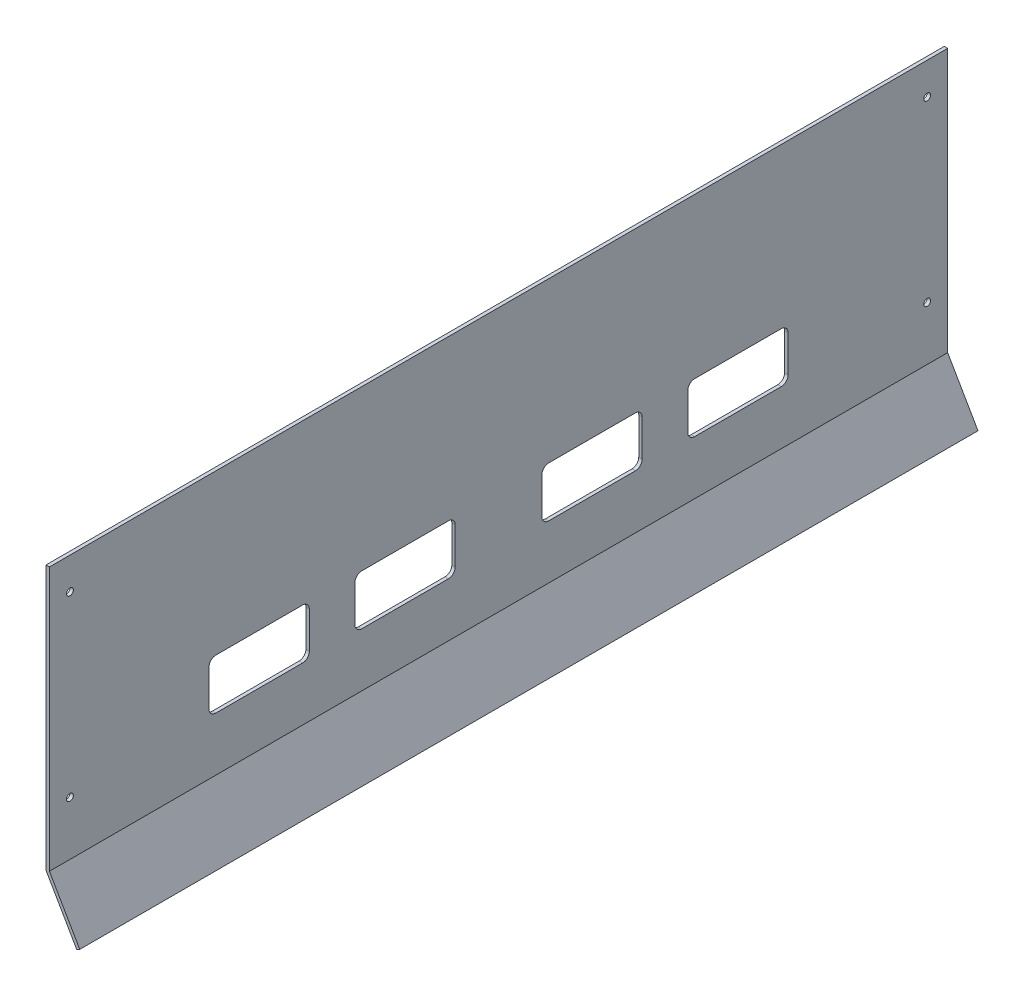
SolidWorks part; units mm, degrees
ref_plane "前视基准面" through (0, 0, 0) normal (0, 0, 1) x (1, 0, 0)
ref_plane "上视基准面" through (0, 0, 0) normal (0, 1, 0) x (1, 0, 0)
ref_plane "右视基准面" through (0, 0, 0) normal (1, 0, 0) x (0, 0, -1)
sketch "草图1" plane through (0, 0, 0) normal (0, 0, 1) x (1, 0, 0)
  line L0 (0, 0) -> (0, 116)
  line L1 (0, 0) -> (13.5, -23.3827)
  line L2 (1.5, 0.4019) -> (14.799, -22.6327)
  line L3 (1.5, 0.4019) -> (1.5, 116)
  line L4 (14.799, -22.6327) -> (13.5, -23.3827)
  line L5 (0, 116) -> (1.5, 116)
  dimension "D1" = 150
  dimension "D2" = 27
  dimension "D3" = 116
  dimension "D4" = 1.5
extrude "凸台-拉伸1" add sketch "草图1" along normal blind 394
sketch "草图2" plane through (0, 0, 0) normal (-1, 0, 0) x (0, 0, 1)
  line L0 (197, 116) -> (197, 0) construction
  line L1 (394, 116) -> (0, 116) construction
  line L2 (394, 0) -> (0, 0) construction
  line L3 (394, 116) -> (394, 0) construction
  line L4 (178, 46) -> (134, 46)
  line L5 (216, 46) -> (260, 46)
  line L6 (216, 46) -> (216, 24)
  line L7 (216, 24) -> (260, 24)
  line L8 (260, 46) -> (260, 24)
  line L9 (280, 46) -> (324, 46)
  line L10 (280, 46) -> (280, 24)
  line L11 (280, 24) -> (324, 24)
  line L12 (324, 46) -> (324, 24)
  line L13 (134, 46) -> (134, 24)
  line L14 (178, 24) -> (134, 24)
  line L15 (178, 46) -> (178, 24)
  line L16 (70, 46) -> (70, 24)
  line L17 (114, 46) -> (70, 46)
  line L18 (114, 46) -> (114, 24)
  line L19 (114, 24) -> (70, 24)
  circle A0 centre (385, 24) radius 1.5
  circle A1 centre (385, 102) radius 1.5
  circle A2 centre (9, 102) radius 1.5
  circle A3 centre (9, 24) radius 1.5
  dimension "D4" = 3
  dimension "D1" = 78
  dimension "D2" = 24
  dimension "D3" = 9
  dimension "D5" = 24
  dimension "D6" = 22
  dimension "D7" = 44
  dimension "D8" = 44
  dimension "D9" = 20
  dimension "D10" = 19
extrude "切除-拉伸1" cut sketch "草图2" against normal through all
fillet "圆角1" radius 3 16 edges at (0.75, 24, 324) (0.75, 46, 324) (0.75, 46, 280) (0.75, 24, 280) (0.75, 46, 260) (0.75, 24, 260) (0.75, 24, 216) (0.75, 46, 216) (0.75, 24, 178) (0.75, 46, 178) (0.75, 46, 134) (0.75, 24, 134) (0.75, 24, 114) (0.75, 46, 114) (0.75, 24, 70) (0.75, 46, 70)
